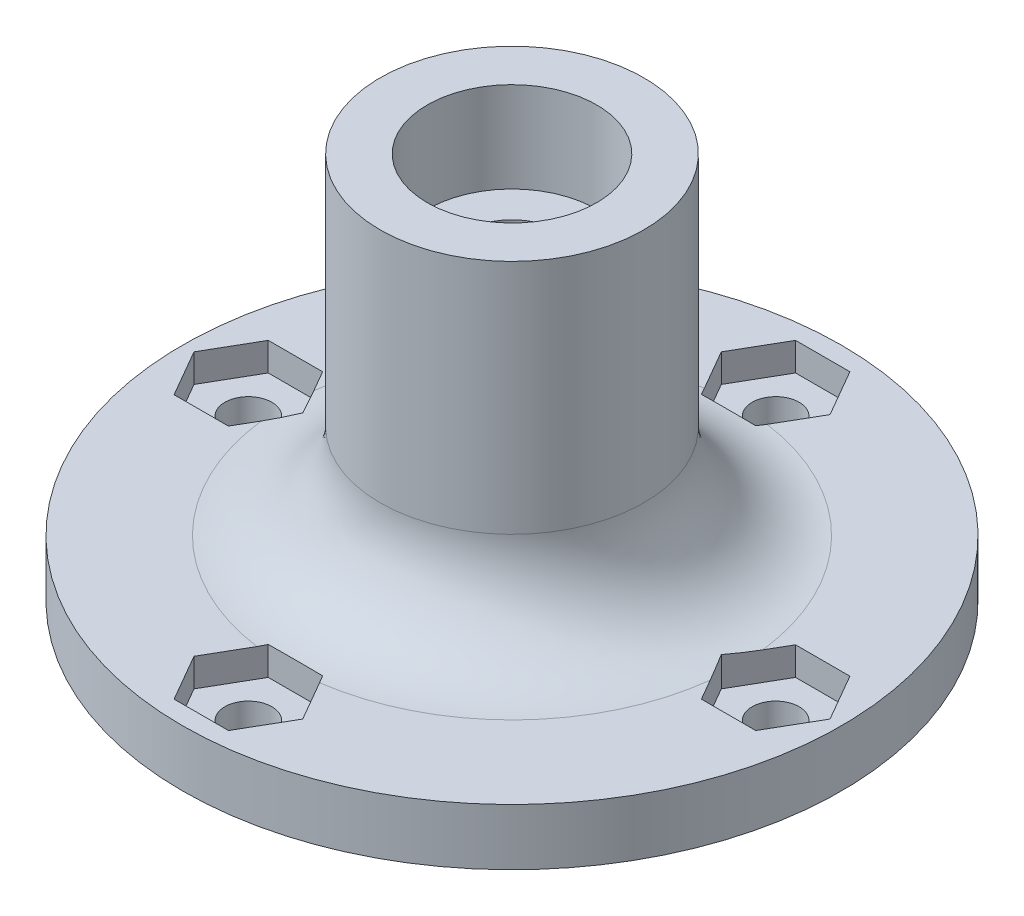
SolidWorks part; units mm, degrees
ref_plane "Front Plane" through (0, 0, 0) normal (0, 0, 1) x (1, 0, 0)
ref_plane "Top Plane" through (0, 0, 0) normal (0, 1, 0) x (1, 0, 0)
ref_plane "Right Plane" through (0, 0, 0) normal (1, 0, 0) x (0, 0, -1)
sketch "Sketch1" plane through (0, 0, 0) normal (0, 1, 0) x (1, 0, 0)
  circle A0 centre (0, 0) radius 17.5
  dimension "D1" = 35
extrude "Boss-Extrude1" add sketch "Sketch1" along normal blind 3
sketch "Sketch2" plane through (0, 3, 0) normal (0, 1, 0) x (1, 0, 0)
  circle A0 centre (0, 0) radius 7
  dimension "D1" = 14
extrude "Boss-Extrude2" add sketch "Sketch2" along normal blind 12.75
sketch "Sketch3" plane through (0, 15.75, 0) normal (0, 1, 0) x (1, 0, 0)
  circle A0 centre (0, 0) radius 7
  circle A1 centre (0, 0) radius 4.5
  dimension "D1" = 9
extrude "Boss-Extrude3" add sketch "Sketch3" along normal blind 4.8
sketch "Sketch4" plane through (0, 15.75, 0) normal (0, 1, 0) x (1, 0, 0)
  circle A0 centre (0, 0) radius 2.5
  dimension "D1" = 5
extrude "Cut-Extrude1" cut sketch "Sketch4" against normal blind 19.8
fillet "Fillet1" radius 5 1 edges at (0, 3, 7)
sketch "Sketch5" plane through (0, 3, 0) normal (0, 1, 0) x (1, 0, 0)
  circle A1 centre (0, 14) radius 1.25
  circle A2 centre (14, 0) radius 1.25
  circle A3 centre (0, -14) radius 1.25
  circle A4 centre (-14, 0) radius 1.25
  dimension "D1" = 2.5
  dimension "D3" = 2.5
  dimension "D6" = 2.5
  dimension "D7" = 2.5
extrude "Cut-Extrude2" cut sketch "Sketch5" against normal blind 3
sketch "Sketch6" plane through (0, 3, 0) normal (0, 1, 0) x (1, 0, 0)
  line L1 (2.8868, 14) -> (1.4434, 16.5)
  line L2 (1.4434, 16.5) -> (-1.4434, 16.5)
  line L3 (-1.4434, 16.5) -> (-2.8868, 14)
  line L4 (-2.8868, 14) -> (-1.4434, 11.5)
  line L5 (-1.4434, 11.5) -> (1.4434, 11.5)
  line L6 (1.4434, 11.5) -> (2.8868, 14)
  line L7 (16.8868, 0) -> (15.4434, 2.5)
  line L8 (15.4434, 2.5) -> (12.5566, 2.5)
  line L9 (12.5566, 2.5) -> (11.1132, 0)
  line L10 (11.1132, 0) -> (12.5566, -2.5)
  line L11 (12.5566, -2.5) -> (15.4434, -2.5)
  line L12 (15.4434, -2.5) -> (16.8868, 0)
  line L13 (2.8868, -14) -> (1.4434, -11.5)
  line L14 (1.4434, -11.5) -> (-1.4434, -11.5)
  line L15 (-1.4434, -11.5) -> (-2.8868, -14)
  line L16 (-2.8868, -14) -> (-1.4434, -16.5)
  line L17 (-1.4434, -16.5) -> (1.4434, -16.5)
  line L18 (1.4434, -16.5) -> (2.8868, -14)
  line L25 (-11.1132, 0) -> (-12.5566, 2.5)
  line L26 (-12.5566, 2.5) -> (-15.4434, 2.5)
  line L27 (-15.4434, 2.5) -> (-16.8868, 0)
  line L28 (-16.8868, 0) -> (-15.4434, -2.5)
  line L29 (-15.4434, -2.5) -> (-12.5566, -2.5)
  line L30 (-12.5566, -2.5) -> (-11.1132, 0)
  circle A0 centre (0, 14) radius 2.5 construction
  circle A1 centre (14, 0) radius 2.5 construction
  circle A2 centre (0, -14) radius 2.5 construction
  circle A3 centre (-14, 0) radius 2.5 construction
  dimension "D1" = 5
  dimension "D2" = 5
  dimension "D3" = 5
  dimension "D4" = 5
extrude "Cut-Extrude3" cut sketch "Sketch6" against normal blind 1.5 and the other way blind 1.5
